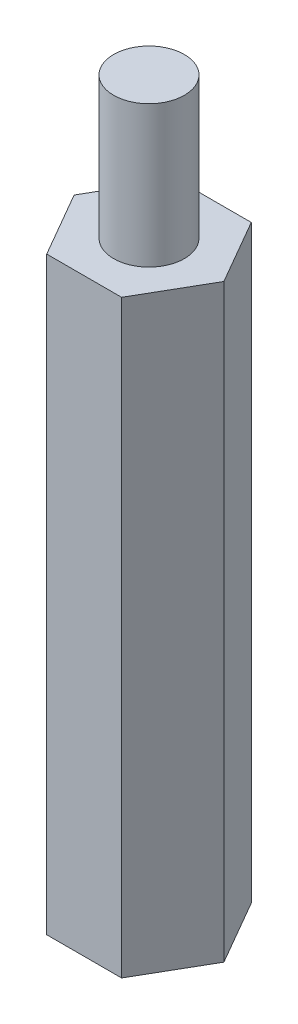
SolidWorks part; units mm, degrees
material "AISI 304"
ref_plane "正面" through (0, 0, 0) normal (0, 0, 1) x (1, 0, 0)
ref_plane "平面" through (0, 0, 0) normal (0, 1, 0) x (1, 0, 0)
ref_plane "右側面" through (0, 0, 0) normal (1, 0, 0) x (0, 0, -1)
sketch "ｽｹｯﾁ1" plane through (0, 0, 0) normal (0, 1, 0) x (1, 0, 0)
  line L1 (1.5877, -2.75) -> (3.1754, 0)
  line L2 (3.1754, 0) -> (1.5877, 2.75)
  line L3 (1.5877, 2.75) -> (-1.5877, 2.75)
  line L4 (-1.5877, 2.75) -> (-3.1754, 0)
  line L5 (-3.1754, 0) -> (-1.5877, -2.75)
  line L6 (-1.5877, -2.75) -> (1.5877, -2.75)
  circle A0 centre (0, 0) radius 2.75 construction
  dimension "D1" = 5.5
extrude "ﾎﾞｽ - 押し出し1" add sketch "ｽｹｯﾁ1" along normal blind 25
sketch "ｽｹｯﾁ2" plane through (0, 25, 0) normal (0, 1, 0) x (1, 0, 0)
  circle A0 centre (0, 0) radius 1.5
  dimension "D1" = 3
extrude "ﾎﾞｽ - 押し出し2" add sketch "ｽｹｯﾁ2" along normal blind 6
cosmetic thread "ねじ山1" parameters "D2"=2
sketch "ｽｹｯﾁ3" plane through (0, 0, 0) normal (0, -1, 0) x (1, 0, 0)
  circle A0 centre (0, 0) radius 1.5
  dimension "D1" = 3
hole_wizard "M3x0.5 ねじ穴1" positions "3Dｽｹｯﾁ2" profile "ｽｹｯﾁ5" tap size "M3x0.5" standard "JIS"
sketch3d "3Dｽｹｯﾁ2"
  point P0 (0, 0, 0)
  point P3 (0, 0, 0)
  point P5 (0, 0, 0)
  point P7 (0, 0, 0)
  point P9 (0, 0, 0)
  dimension "D1" = 0
sketch "ｽｹｯﾁ5" plane through (0, 0, 0) normal (1, 0, 0) x (0, 0, -1)
  line L0 (0, 0) -> (0, 9.2511)
  line L1 (0, 9.2511) -> (1.25, 8.5)
  line L2 (1.25, 8.5) -> (1.25, 0)
  line L5 (1.25, 0) -> (0, 0)
  line L10 (0, 9.2511) -> (-1.25, 8.5) construction
  line L11 (0, -6.35) -> (0, 107.95) construction
  dimension "ねじ下穴ﾄﾞﾘﾙ直径" = 2.5
  dimension "ねじ下穴ﾄﾞﾘﾙの深さ" = 8.5
  dimension "ﾄﾞﾘﾙ角度" = 118
cosmetic thread "穴のねじ山1" parameters "D1"=6, "D2"=3
cosmetic thread "穴のねじ山2" parameters "D1"=6, "D2"=3
cosmetic thread "穴のねじ山3" parameters "D1"=6, "D2"=3
cosmetic thread "穴のねじ山4" parameters "D1"=6, "D2"=3
cosmetic thread "穴のねじ山5" parameters "D1"=6, "D2"=3
